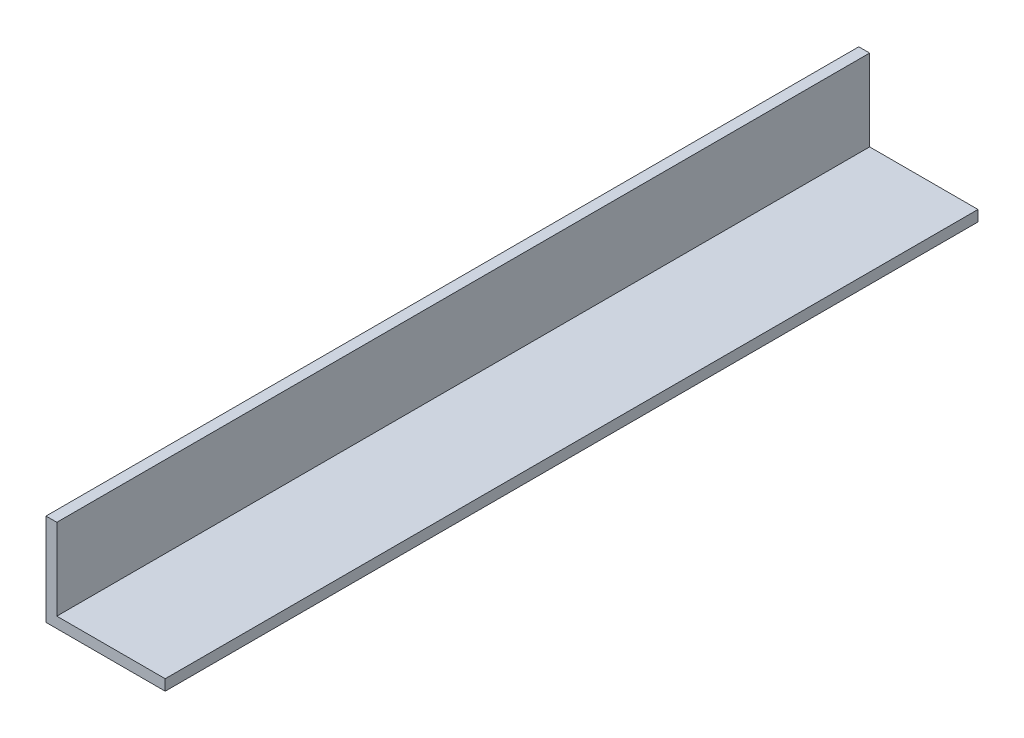
SolidWorks part; units mm, degrees
ref_plane "Front Plane" through (0, 0, 0) normal (0, 0, 1) x (1, 0, 0)
ref_plane "Top Plane" through (0, 0, 0) normal (0, 1, 0) x (1, 0, 0)
ref_plane "Right Plane" through (0, 0, 0) normal (1, 0, 0) x (0, 0, -1)
sketch "Sketch1" plane through (0, 0, 0) normal (0, 0, 1) x (1, 0, 0)
  line L0 (0, 0) -> (0, 17)
  line L1 (0, 17) -> (2, 17)
  line L2 (2, 17) -> (2, 2)
  line L3 (2, 2) -> (22, 2)
  line L4 (22, 2) -> (22, 0)
  line L5 (22, 0) -> (0, 0)
  dimension "D1" = 17
  dimension "D2" = 2
  dimension "D3" = 2
  dimension "D4" = 22
extrude "Boss-Extrude1" add sketch "Sketch1" along normal blind 150
